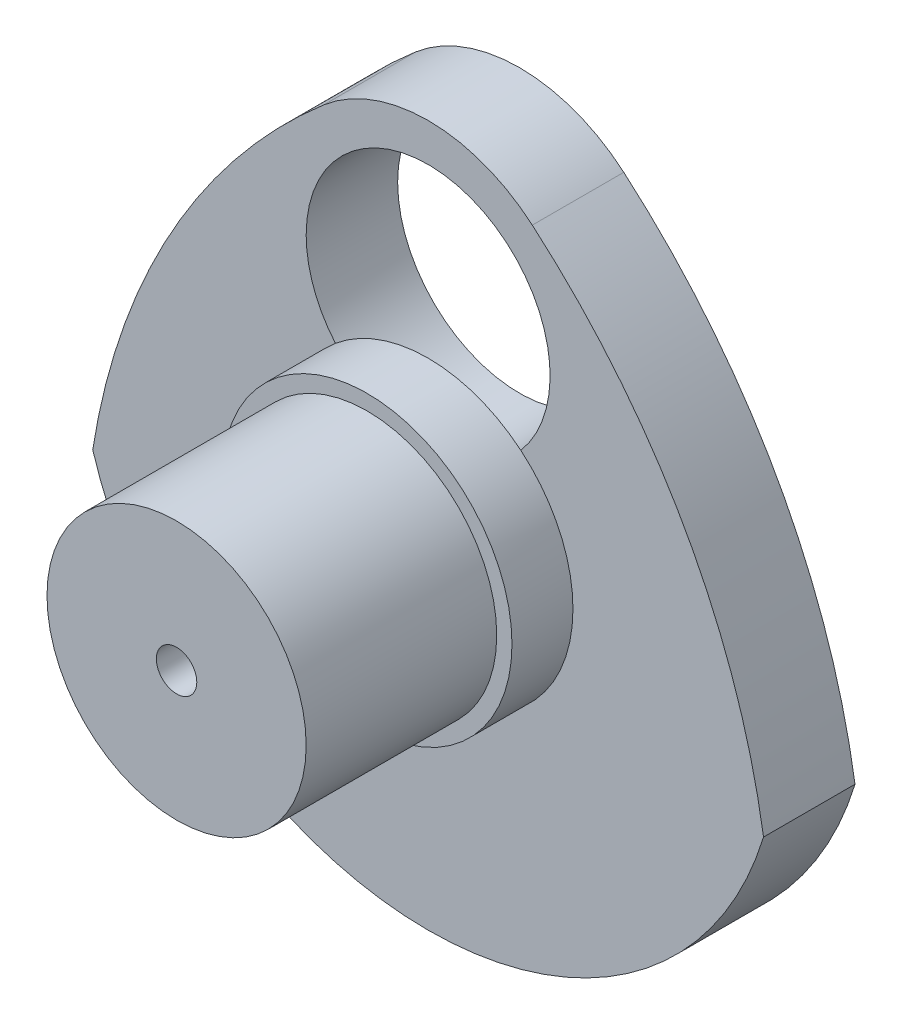
SolidWorks part; units mm, degrees
ref_plane "Front Plane" through (0, 0, 0) normal (0, 0, 1) x (1, 0, 0)
ref_plane "Top Plane" through (0, 0, 0) normal (0, 1, 0) x (1, 0, 0)
ref_plane "Right Plane" through (0, 0, 0) normal (1, 0, 0) x (0, 0, -1)
sketch "Sketch3" plane through (0, 0, 0) normal (0, 0, 1) x (1, 0, 0)
  circle A0 centre (0, 0) radius 17
  dimension "D1" = 34
extrude "Boss-Extrude2" add sketch "Sketch3" along normal blind 25
sketch "Sketch4" plane through (0, 0, 0) normal (0, 0, 1) x (1, 0, 0)
  circle A0 centre (0, 0) radius 19
  dimension "D1" = 38
extrude "Boss-Extrude3" add sketch "Sketch4" against normal blind 8
sketch "Sketch5" plane through (0, 0, -8) normal (0, 0, -1) x (-1, 0, 0)
  line L0 (0, 46) -> (0, -29.9234) construction
  arc A0 (-44, -13.4164) -> (44, -13.4164) centre (0, 0) ccw
  arc A1 (13.6681, 40.9431) -> (-13.6681, 40.9431) centre (0, 25) ccw
  arc A2 (-13.6681, 40.9431) -> (-44, -13.4164) centre (44.9095, -27.3845) ccw
  arc A3 (13.6681, 40.9431) -> (44, -13.4164) centre (-44.9095, -27.3845) cw
  dimension "D2" = 46
  dimension "D3" = 42
  dimension "D5" = 90
  dimension "D6" = 90
  dimension "D1" = 88
  dimension "D4" = 25
  dimension "D7" = 25
extrude "Boss-Extrude4" add sketch "Sketch5" along normal blind 12
sketch "Sketch9" plane through (0, 0, -20) normal (0, 0, -1) x (-1, 0, 0)
  circle A0 centre (0, 25) radius 16
  dimension "D1" = 32
extrude "Cut-Extrude1" cut sketch "Sketch9" against normal blind 12
sketch "Sketch10" plane through (0, 0, 25) normal (0, 0, 1) x (1, 0, 0)
  circle A0 centre (0, 0) radius 2.65
  dimension "D1" = 5.3
extrude "Cut-Extrude2" cut sketch "Sketch10" against normal blind 15
